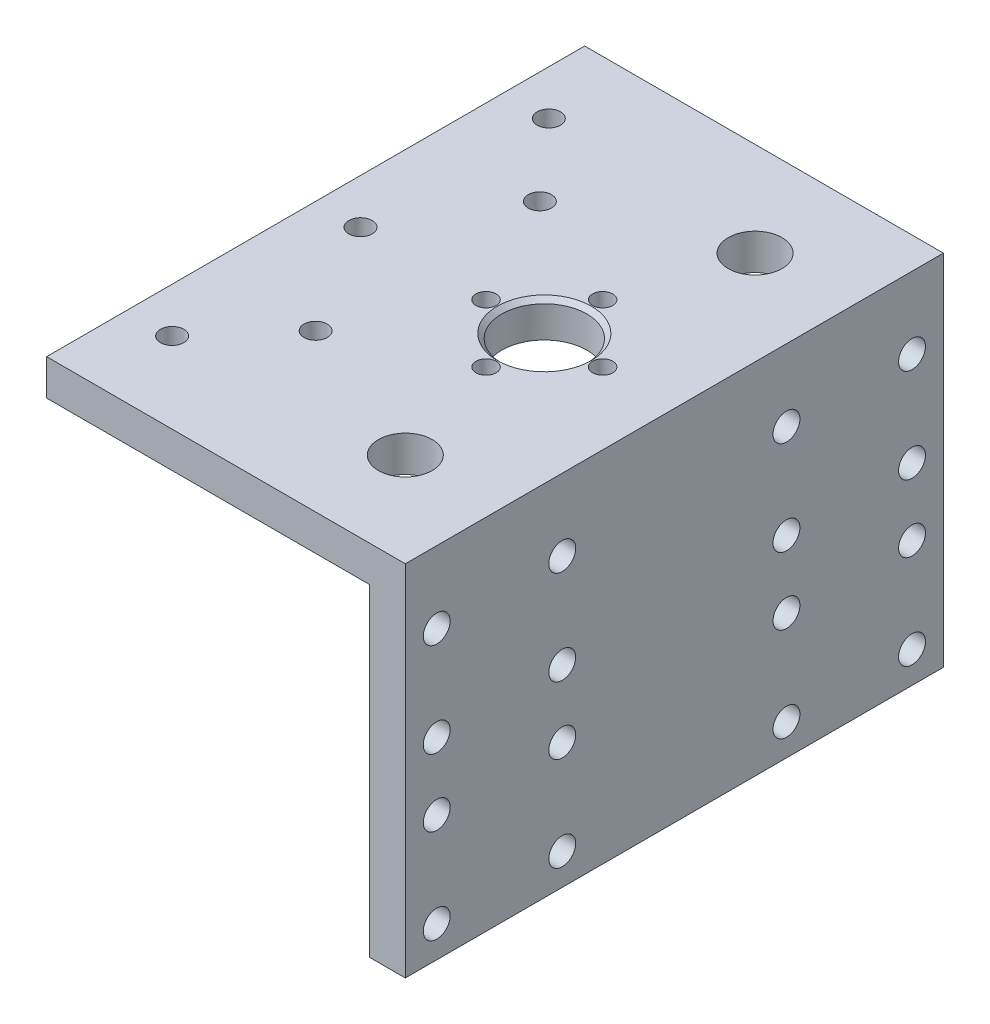
SolidWorks part; units mm, degrees
material "Lega 1060"
ref_plane "Piano frontale" through (0, 0, 0) normal (0, 0, 1) x (1, 0, 0)
ref_plane "Piano superiore" through (0, 0, 0) normal (0, 1, 0) x (1, 0, 0)
ref_plane "Piano destro" through (0, 0, 0) normal (1, 0, 0) x (0, 0, -1)
sketch "Schizzo1" plane through (0, 0, 0) normal (0, 0, 1) x (1, 0, 0)
  line L0 (0, 0) -> (-80, 0)
  line L1 (-80, 0) -> (-80, -8)
  line L2 (-80, -8) -> (-8, -8)
  line L3 (-8, -8) -> (-8, -80)
  line L4 (-8, -80) -> (0, -80)
  line L5 (0, -80) -> (0, 0)
  dimension "D1" = 80
  dimension "D2" = 80
  dimension "D3" = 8
  dimension "D4" = 8
extrude "Estrusione-Estrusione1" add sketch "Schizzo1" along normal blind 120
sketch "Schizzo12" plane through (0, 0, 0) normal (1, 0, 0) x (0, 0, -1)
  line L0 (0, -8) -> (-120, -8) construction
  line L1 (-21, 0) -> (-21, 18.8536) construction
  line L2 (-60, 0) -> (-60, -80) construction
  line L3 (-120, -80) -> (0, -80) construction
  line L5 (0, -80) -> (0, 0) construction
  line L6 (-120, -80) -> (-120, 0) construction
  line L7 (-120, 0) -> (0, 0) construction
  line L10 (-99, -47.4454) -> (-99, 40.839) construction
  line L11 (-128.3276, -73) -> (20.444, -73) construction
  line L13 (-134.9226, -44.5) -> (16.1501, -44.5) construction
  circle A0 centre (-35, -73) radius 3
  circle A1 centre (-7, -73) radius 3
  circle A2 centre (-113, -73) radius 3
  circle A3 centre (-85, -73) radius 3
  circle A4 centre (-85, -52) radius 3
  circle A5 centre (-113, -52) radius 3
  circle A6 centre (-35, -52) radius 3
  circle A7 centre (-7, -52) radius 3
  circle A8 centre (-85, -16) radius 3
  circle A9 centre (-113, -16) radius 3
  circle A10 centre (-35, -37) radius 3
  circle A11 centre (-7, -37) radius 3
  circle A12 centre (-35, -16) radius 3
  circle A13 centre (-7, -16) radius 3
  circle A14 centre (-85, -37) radius 3
  circle A15 centre (-113, -37) radius 3
  dimension "D5" = 6
  dimension "D6" = 43
  dimension "D7" = 64
  dimension "D13" = 35.5
  dimension "D2" = 8
  dimension "D3" = 21
  dimension "D4" = 28
  dimension "D9" = 21
  dimension "D10" = 21
  dimension "D11" = 7
sketch "Schizzo6" plane through (0, 0, 0) normal (0, 1, 0) x (1, 0, 0)
  line L0 (-21, -0.5808) -> (-21, -110.5835) construction
  line L2 (0, 0) -> (-80, 0) construction
  line L3 (-32.5218, -60) -> (-8.0464, -60) construction
  line L6 (0, -120) -> (-80, -120) construction
  circle A0 centre (-21, -21) radius 6
  circle A1 centre (-21, -99) radius 6
  dimension "D2" = 12
  dimension "D1" = 13
  dimension "D3" = 21
extrude "Taglio-Estrusione2" cut sketch "Schizzo6" against normal up to next
sketch "Schizzo7" plane through (0, 0, 0) normal (0, 1, 0) x (1, 0, 0)
  line L0 (-53.636, -60) -> (3.6289, -60) construction
  line L1 (0, -120) -> (-80, -120) construction
  line L2 (0, 0) -> (-80, 0) construction
  line L3 (-21, -21) -> (-21, -99) construction
  circle A0 centre (-29, -60) radius 9.5
  dimension "D1" = 19
  dimension "D2" = 8
extrude "Taglio-Estrusione3" cut sketch "Schizzo7" against normal up to next
hole_wizard "Foro per Vite M4-2" positions "Schizzo9" profile "Schizzo8" hole size "M4" standard "ISO" end condition through all
sketch "Schizzo9" plane through (0, 0, 0) normal (0, 1, 0) x (1, 0, 0)
  line L0 (-18.4657, -60) -> (-16, -60) construction
  line L2 (-29, -57.7684) -> (-29, -66.5063) construction
  circle A2 centre (-29, -60) radius 9.5 construction
  point P0 (-29, -47)
  point P2 (-42, -60)
  point P4 (-29, -73)
  point P8 (-16, -60)
  point P20 (-29, -60)
  dimension "D1" = 26
  dimension "D2" = 13
  dimension "D3" = 13
sketch "Schizzo8" plane through (-29, 0, 47) normal (1, 0, 0) x (0, 0, 1)
  line L0 (0, 0) -> (0, 80)
  line L1 (0, 80) -> (2.25, 80)
  line L2 (2.25, 80) -> (2.25, 0)
  line L5 (2.25, 0) -> (0, 0)
  line L11 (0, -6.35) -> (0, 107.95) construction
  dimension "Thru Hole Dia." = 4.5
  dimension "Thru Hole Depth" = 80
extrude "Taglio-Estrusione4" cut sketch "Schizzo12" against normal blind 10
sketch "Schizzo14" plane through (0, 0, 0) normal (0, 1, 0) x (1, 0, 0)
  line L0 (-70, 0) -> (-70, -120) construction
  line L1 (0, 0) -> (-80, 0) construction
  line L2 (0, -120) -> (-80, -120) construction
  line L3 (-80, -120) -> (-80, 0) construction
  line L4 (-55, 0) -> (-55, -120) construction
  line L5 (-21, -99) -> (-80, -99) construction
  line L6 (-80, -60) -> (0, -60) construction
  line L7 (0, -120) -> (0, 0) construction
  line L8 (-21, -21) -> (-80, -21) construction
  circle A0 centre (-70, -18) radius 2.6
  circle A1 centre (-70, -60) radius 2.6
  circle A2 centre (-70, -102) radius 2.6
  circle A3 centre (-55, -35) radius 2.6
  circle A4 centre (-55, -85) radius 2.6
  dimension "D3" = 5.2
  dimension "D4" = 5.2
  dimension "D5" = 5.2
  dimension "D6" = 5.2
  dimension "D7" = 5.2
  dimension "D1" = 10
  dimension "D2" = 25
  dimension "D8" = 35
  dimension "D9" = 35
  dimension "D10" = 25
  dimension "D11" = 42
  dimension "D12" = 15
extrude "Taglio-Estrusione5" cut sketch "Schizzo14" against normal blind 10
chamfer "Smusso2" distance 1 angle 45 1 edges at (-38.5, 0, 60)
